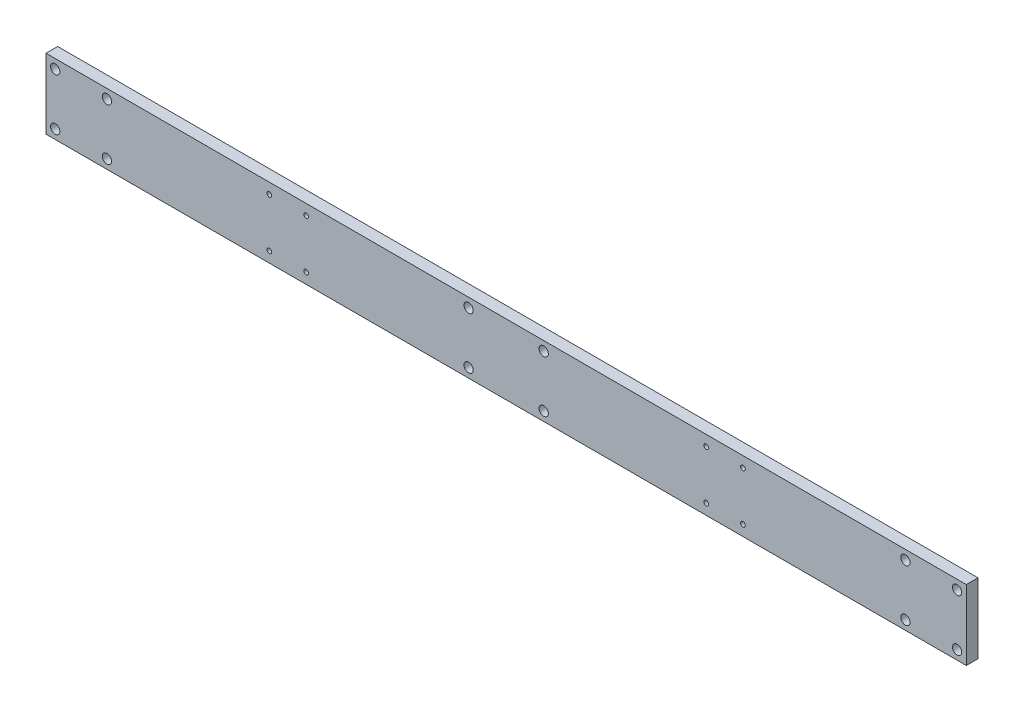
SolidWorks part; units mm, degrees
material "6061-O (SS)"
ref_plane "Alzado" through (0, 0, 0) normal (0, 0, 1) x (1, 0, 0)
ref_plane "Planta" through (0, 0, 0) normal (0, 1, 0) x (1, 0, 0)
ref_plane "Vista lateral" through (0, 0, 0) normal (1, 0, 0) x (0, 0, -1)
sketch "Croquis1" plane through (0, 0, 0) normal (0, 0, 1) x (1, 0, 0)
  line L1 (-500, 38.1) -> (500, 38.1)
  line L2 (-500, 38.1) -> (-500, -38.1)
  line L3 (-500, -38.1) -> (500, -38.1)
  line L4 (500, 38.1) -> (500, -38.1)
  line L5 (-500, 38.1) -> (500, -38.1) construction
  line L6 (-500, -38.1) -> (500, 38.1) construction
  point P0 (0, 0)
  dimension "D1" = 76.2
  dimension "D2" = 1000
extrude "Saliente-Extruir1" add sketch "Croquis1" along normal mid plane 12.7
hole_wizard "Taladro de margen para 3/81" positions "Croquis2" profile "Croquis3" hole size "3/8" standard "Ansi Inch" end condition through all
sketch "Croquis2" plane through (0, 0, -6.35) normal (0, 0, -1) x (-1, 0, 0)
  line L0 (0, 0) -> (50000, 0) construction
  line L4 (0, 0) -> (0, 50000) construction
  point P0 (433.8, 28.1)
  point P2 (490, 28.1)
  point P24 (490, -28.1)
  point P25 (433.8, -28.1)
  point P26 (-433.8, -28.1)
  point P27 (-490, -28.1)
  point P28 (-490, 28.1)
  point P29 (-433.8, 28.1)
  point P34 (40.8, 28.1)
  point P40 (40.8, -28.1)
  point P42 (-40.8, 28.1)
  point P43 (-40.8, -28.1)
sketch "Croquis3" plane through (-433.8, 28.1, -6.35) normal (1, 0, 0) x (0, 1, 0)
  line L0 (0, 0) -> (0, 12.7)
  line L1 (0, 12.7) -> (5.0419, 12.7)
  line L2 (5.0419, 12.7) -> (5.0419, 0)
  line L5 (5.0419, 0) -> (0, 0)
  line L11 (0, -6.35) -> (0, 107.95) construction
  dimension "Diámetro de taladro hasta el siguiente" = 10.0838
  dimension "Profundidad de taladro hasta el siguiente" = 12.7
hole_wizard "#10 Clearance Hole1" positions "Sketch1" profile "Sketch2" hole size "#10" standard "ANSI Inch" end condition through all
sketch "Sketch1" plane through (0, 0, -6.35) normal (0, 0, -1) x (-1, 0, 0)
  line L0 (217.3, 26.5) -> (257.3, 26.5) construction
  line L1 (217.3, 26.5) -> (217.3, -26.5) construction
  line L2 (40.8, 28.1) -> (433.8, 28.1) construction
  line L3 (40.8, 28.1) -> (40.8, -28.1) construction
  line L5 (0, 0) -> (0, 50000) construction
  point P0 (217.3, 26.5)
  point P10 (257.3, 26.5)
  point P11 (257.3, -26.5)
  point P12 (217.3, -26.5)
  point P23 (237.3, 26.5)
  point P24 (237.3, 28.1)
  point P31 (40.8, 0)
  point P32 (217.3, 0)
  point P43 (-257.3, 26.5)
  point P44 (-257.3, -26.5)
  point P45 (-217.3, -26.5)
  point P46 (-217.3, 26.5)
  dimension "D2" = 90
  dimension "D3" = 40
  dimension "D4" = 53
  dimension "D1" = 2
  dimension "D5" = 2
sketch "Sketch2" plane through (-217.3, 26.5, -6.35) normal (1, 0, 0) x (0, 1, 0)
  line L0 (0, 0) -> (0, 12.7)
  line L1 (0, 12.7) -> (2.5527, 12.7)
  line L2 (2.5527, 12.7) -> (2.5527, 0)
  line L5 (2.5527, 0) -> (0, 0)
  line L11 (0, -6.35) -> (0, 107.95) construction
  dimension "Thru Hole Dia." = 5.1054
  dimension "Thru Hole Depth" = 12.7
